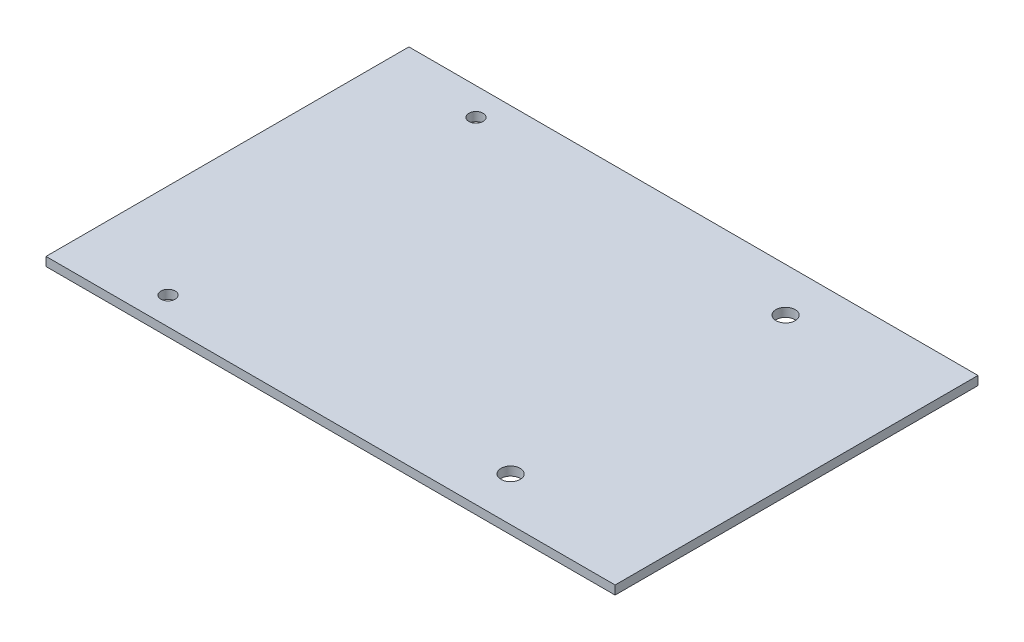
SolidWorks part; units mm, degrees
ref_plane "Front Plane" through (0, 0, 0) normal (0, 0, 1) x (1, 0, 0)
ref_plane "Top Plane" through (0, 0, 0) normal (0, 1, 0) x (1, 0, 0)
ref_plane "Right Plane" through (0, 0, 0) normal (1, 0, 0) x (0, 0, -1)
sketch "Sketch1" plane through (0, 0, 0) normal (0, 1, 0) x (1, 0, 0)
  line L1 (-51.75, -33) -> (51.75, -33)
  line L2 (-51.75, -33) -> (-51.75, 33)
  line L3 (-51.75, 33) -> (51.75, 33)
  line L4 (51.75, -33) -> (51.75, 33)
  line L5 (-51.75, -33) -> (51.75, 33) construction
  line L6 (-51.75, 33) -> (51.75, -33) construction
  point P0 (0, 0)
  dimension "D1" = 103.5
  dimension "D2" = 66
extrude "Boss-Extrude1" add sketch "Sketch1" along normal blind 1.6
sketch "Sketch2" plane through (0, 1.6, 0) normal (0, 1, 0) x (1, 0, 0)
  line L0 (-51.75, 33) -> (-51.75, -33) construction
  circle A6 centre (-16.77, 28) radius 3
  circle A7 centre (-16.77, -28) radius 3
  dimension "D1" = 34.98
  dimension "D2" = 56
  dimension "D3" = 28
extrude "Cut-Extrude1" [suppressed] cut sketch "Sketch2" against normal blind 1.6
sketch "Sketch3" plane through (0, 1.6, 0) normal (0, 1, 0) x (1, 0, 0)
  line L1 (-51.75, 33) -> (-51.75, -33) construction
  line L2 (0, 0) -> (-54.2874, 0) construction
  line L3 (51.75, 33) -> (-51.75, 33) construction
  circle A0 centre (-34.5523, 28) radius 1.3
  circle A6 centre (-34.5523, -28) radius 1.3
  dimension "D1" = 2.6
  dimension "D3" = 17.1977
  dimension "D4" = 56
  dimension "D5" = 5
  dimension "D2" = 17.1977
extrude "Cut-Extrude2" cut sketch "Sketch3" against normal blind 10
sketch "Sketch4" plane through (0, 1.6, 0) normal (0, 1, 0) x (1, 0, 0)
  line L0 (51.75, -33) -> (51.75, 33) construction
  line L1 (51.75, 33) -> (-51.75, 33) construction
  line L3 (-51.75, -33) -> (51.75, -33) construction
  circle A0 centre (24.75, 25) radius 1.75
  circle A1 centre (24.75, -25) radius 1.75
  dimension "D1" = 3.5
  dimension "D2" = 27
  dimension "D3" = 8
  dimension "D4" = 8
extrude "Cut-Extrude3" cut sketch "Sketch4" against normal up to next
